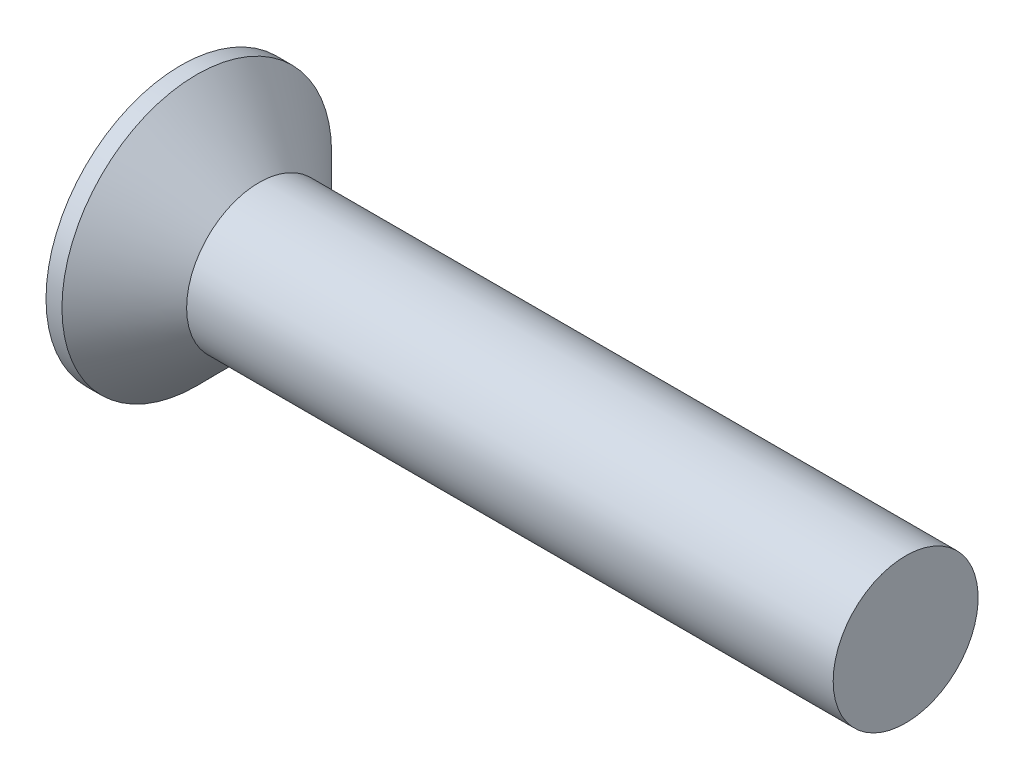
SolidWorks part; units mm, degrees
revolve "Base-Revolve" add sketch "BodySke" angle 360 about L5
sketch "BodySke" plane through (0, 0, 0) normal (0, 0, 1) x (1, 0, 0)
  line L0 (0, 0) -> (0, 4.65)
  line L1 (0, 4.65) -> (0.55, 4.65)
  line L2 (2.7, 2.5) -> (25, 2.5)
  line L3 (25, 2.5) -> (25, 0)
  line L4 (25, 0) -> (0, 0)
  line L5 (-6.35, 0) -> (82.55, 0) construction
  line L6 (2.7, -2.5) -> (25, -2.5) construction
  line L7 (0.55, -4.65) -> (2.7, -2.5) construction
  line L8 (0.55, 4.65) -> (2.7, 2.5)
  line L9 (0, -4.65) -> (0.55, -4.65) construction
  line L10 (3.5, 4.0875) -> (3.5, -5.4375) construction
  line L11 (0, 6.35) -> (0, -3.175) construction
  dimension "Length" = 25
  dimension "Head_ht" = 2.7
  dimension "Head_ang" = 90
  dimension "Thread_nom" = 25
cosmetic thread "ThreadCosmetic" [suppressed] parameters "Thread_length"=21.5, "Thread_minor"=4.11
extrude "Slot" [suppressed] cut sketch "Sketch2" against normal blind 1.4
sketch "Sketch2" plane through (0, 0, 0) normal (-1, 0, 0) x (0, 0, 1)
  line L0 (-4.65, -0.75) -> (4.65, -0.75)
  line L1 (-4.65, -0.75) -> (-4.65, 0.75)
  line L2 (4.65, 0.75) -> (-4.65, 0.75)
  line L3 (4.65, 0.75) -> (4.65, -0.75)
  dimension "Slot_width" = 1.5
  dimension "D1" = 0.75
ref_plane "Plane1" through (0, 0, 0) normal (0, 0, 1) x (1, 0, 0)
ref_plane "Plane2" through (0, 0, 0) normal (0, 1, 0) x (1, 0, 0)
ref_plane "Plane3" through (0, 0, 0) normal (1, 0, 0) x (0, 0, -1)
sketch "Sketch3" plane through (0, 0, 0) normal (-1, 0, 0) x (0, 0, 1)
  line L0 (-0.52, 2.53) -> (0.52, 2.53)
  line L1 (0.52, 2.53) -> (0.52, -2.53)
  line L2 (0.52, -2.53) -> (-0.52, -2.53)
  line L3 (-0.52, -2.53) -> (-0.52, 2.53)
ref_plane "Plane4" through (3.35, 0, 0) normal (-1, 0, 0) x (0, 0, 1)
sketch "Sketch4" plane through (3.35, 0, 0) normal (-1, 0, 0) x (0, 0, 1)
  line L0 (-0.26, 0.26) -> (0.26, 0.26)
  line L3 (0.26, 0.26) -> (0.26, -0.26)
  line L4 (0.26, -0.26) -> (-0.26, -0.26)
  line L5 (-0.26, -0.26) -> (-0.26, 0.26)
loft "Cross" cut profiles "Sketch3", "Sketch4"
pattern_circular "CirPattern1" count 2 every 90 about axis through (0, 0, 0) along (1, 0, 0) of "Cross"
sketch "ThdSchSke" plane through (0, 0, 0) normal (0, 0, 1) x (1, 0, 0)
  line L0 (3.5, -2.055) -> (3.1884, -2.5)
  line L1 (3.5, -2.055) -> (3.8116, -2.5)
  line L2 (3.8116, -2.5) -> (3.8116, -3.125)
  line L3 (-3.175, 0) -> (5.1513, 0) construction
  line L5 (3.8116, -3.125) -> (3.1884, -3.125)
  line L6 (3.1884, -3.125) -> (3.1884, -2.5)
  line L7 (0, 4.65) -> (0, -4.65) construction
revolve "ThreadSchematic" [suppressed] cut sketch "ThdSchSke" angle 360 about L3
pattern_linear "ThdSchPat" [suppressed]
equation "\"D1@Sketch3\" = \"Cross_dia@Sketch3\" / 2"
equation "\"D2@Sketch3\" = \"Cross_width@Sketch3\" / 2"
equation "\"D1@Sketch4\" = \"Cross_width@Sketch3\" *.5"
equation "\"D2@Sketch4\" = \"D1@Sketch4\""
equation "\"D4@Sketch4\" = \"D2@Sketch4\" / 2"
equation "\"D3@Sketch4\" = \"D1@Sketch4\" / 2"
equation "\"D1@Sketch2\" = \"Slot_width@Sketch2\" / 2"
equation "\"D2@Sketch2\" = \"Head_dia@BodySke\""
equation "\"D3@Sketch2\" = \"D2@Sketch2\" / 2"
equation "\"Thread_length@ThreadCosmetic\" = ((sgn( (\"Length@BodySke\" - \"Advance@BodySke\" - \"Head_ht@BodySke\" ) - \"Thread_nom@BodySke\" )-1)*( (\"Length@BodySke\" - \"Advance@BodySke\" - \"Head_ht@BodySke\" ) - \"Thread_nom@BodySke\" ))/-2+ \"Thread_nom@BodySke\""
equation "\"Thread_minor@ThdSchSke\" = \"Thread_minor@ThreadCosmetic\""
equation "\"Diameter@ThdSchSke\" = \"Diameter@BodySke\""
equation "\"Overcut@ThdSchSke\" = \"Diameter@BodySke\" * 1.25"
equation "\"Start@ThdSchSke\" = 0.000001 + \"Length@BodySke\" - \"Thread_length@ThreadCosmetic\"  '---Countersunk---"
equation "\"Num_threads@ThdSchPat\" = int( \"Thread_length@ThreadCosmetic\" / \"Advance@BodySke\" + 0.999 )  + 1"
equation "\"Advance@ThdSchPat\" = \"Thread_length@ThreadCosmetic\" /  (\"Num_threads@ThdSchPat\" - 1) 'relax it"
